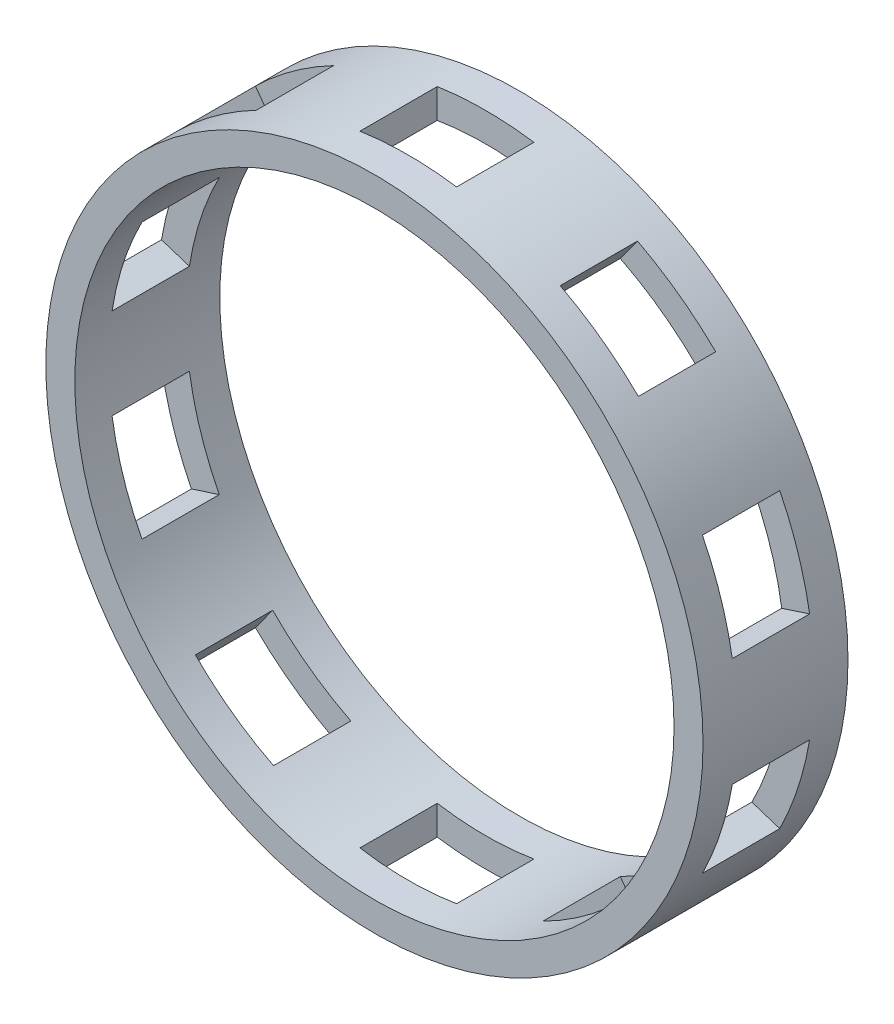
SolidWorks part; units mm, degrees
ref_plane "Front Plane" through (0, 0, 0) normal (0, 0, 1) x (1, 0, 0)
ref_plane "Top Plane" through (0, 0, 0) normal (0, 1, 0) x (1, 0, 0)
ref_plane "Right Plane" through (0, 0, 0) normal (1, 0, 0) x (0, 0, -1)
sketch "Sketch1" plane through (0, 0, 0) normal (0, 0, 1) x (1, 0, 0)
  circle A0 centre (0, 0) radius 68
  circle A1 centre (0, 0) radius 62
extrude "Boss-Extrude1" add sketch "Sketch1" along normal blind 30
sketch "Sketch2" plane through (0, 0, 0) normal (0, 1, 0) x (1, 0, 0)
  line L0 (0, 0) -> (0, -30) construction
  line L1 (-68, -30) -> (68, -30) construction
  line L3 (-10, -23) -> (10, -23)
  line L4 (-10, -23) -> (-10, -7)
  line L5 (-10, -7) -> (10, -7)
  line L6 (10, -23) -> (10, -7)
  line L7 (-10, -23) -> (10, -7) construction
  line L8 (-10, -7) -> (10, -23) construction
  point P5 (0, -15)
extrude "Cut-Extrude1" cut sketch "Sketch2" against normal through all both and the other way through all
pattern_circular "CirPattern1" count 5 over 360 about axis through (0, 0, 0) along (0, 0, 1) of "Cut-Extrude1"
